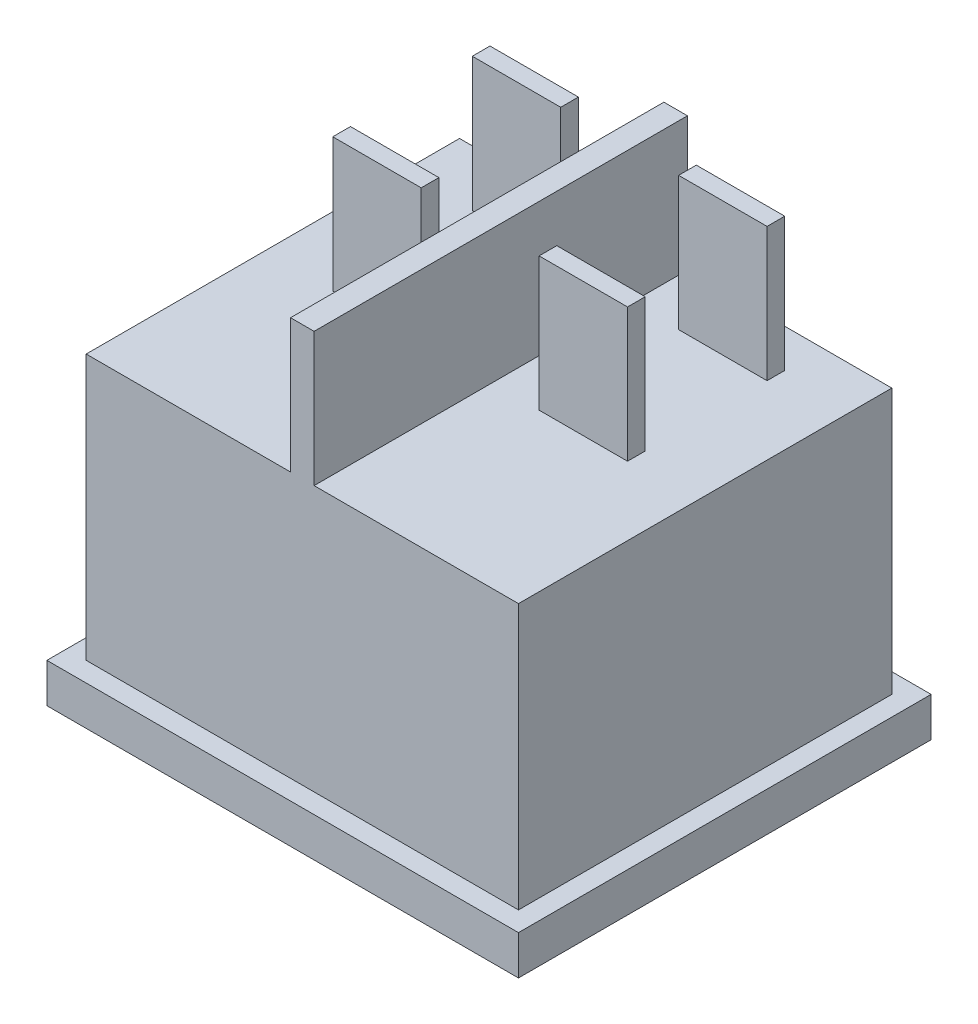
SolidWorks part; units mm, degrees
ref_plane "Front Plane" through (0, 0, 0) normal (0, 0, 1) x (1, 0, 0)
ref_plane "Top Plane" through (0, 0, 0) normal (0, 1, 0) x (1, 0, 0)
ref_plane "Right Plane" through (0, 0, 0) normal (1, 0, 0) x (0, 0, -1)
sketch "Sketch1" plane through (0, 0, 0) normal (0, 1, 0) x (1, 0, 0)
  line L1 (-12, -10.5) -> (12, -10.5)
  line L2 (-12, -10.5) -> (-12, 10.5)
  line L3 (-12, 10.5) -> (12, 10.5)
  line L4 (12, -10.5) -> (12, 10.5)
  line L5 (-12, -10.5) -> (12, 10.5) construction
  line L6 (-12, 10.5) -> (12, -10.5) construction
  point P0 (0, 0)
  dimension "D1" = 24
  dimension "D2" = 21
extrude "Boss-Extrude1" add sketch "Sketch1" along normal blind 2
sketch "Sketch2" plane through (0, 2, 0) normal (0, 1, 0) x (1, 0, 0)
  line L1 (-11, -9.5) -> (11, -9.5)
  line L2 (-11, -9.5) -> (-11, 9.5)
  line L3 (-11, 9.5) -> (11, 9.5)
  line L4 (11, -9.5) -> (11, 9.5)
  line L5 (-11, -9.5) -> (11, 9.5) construction
  line L6 (-11, 9.5) -> (11, -9.5) construction
  point P0 (0, 0)
  dimension "D1" = 22
  dimension "D2" = 19
extrude "Boss-Extrude2" add sketch "Sketch2" along normal blind 13.5
sketch "Sketch3" plane through (0, 15.5, 0) normal (0, 1, 0) x (1, 0, 0)
  line L0 (11, 9.5) -> (-11, 9.5) construction
  line L1 (-0.6, -9.5) -> (0.6, -9.5)
  line L2 (-0.6, -9.5) -> (-0.6, 9.5)
  line L3 (-0.6, 9.5) -> (0.6, 9.5)
  line L4 (0.6, -9.5) -> (0.6, 9.5)
  line L5 (-0.6, -9.5) -> (0.6, 9.5) construction
  line L6 (-0.6, 9.5) -> (0.6, -9.5) construction
  point P0 (0, 0)
  dimension "D1" = 1.2
extrude "Boss-Extrude3" add sketch "Sketch3" along normal blind 6.8
sketch "Sketch4" plane through (0, 15.5, 0) normal (0, 1, 0) x (1, 0, 0)
  line L0 (-3, 7.55) -> (3, 7.55) construction
  line L1 (-7.5, 6.65) -> (-3, 6.65)
  line L2 (-7.5, 6.65) -> (-7.5, 7.55)
  line L3 (-7.5, 7.55) -> (-3, 7.55)
  line L4 (-3, 6.65) -> (-3, 7.55)
  line L5 (-7.5, 6.65) -> (-3, 7.55) construction
  line L6 (-7.5, 7.55) -> (-3, 6.65) construction
  line L7 (-7.5, -0.45) -> (-3, -0.45)
  line L8 (-7.5, -0.45) -> (-7.5, 0.45)
  line L9 (-7.5, 0.45) -> (-3, 0.45)
  line L10 (-3, -0.45) -> (-3, 0.45)
  line L11 (-7.5, -0.45) -> (-3, 0.45) construction
  line L12 (-7.5, 0.45) -> (-3, -0.45) construction
  line L13 (3, 6.65) -> (7.5, 6.65)
  line L14 (3, 6.65) -> (3, 7.55)
  line L15 (3, 7.55) -> (7.5, 7.55)
  line L16 (7.5, 6.65) -> (7.5, 7.55)
  line L17 (3, 6.65) -> (7.5, 7.55) construction
  line L18 (3, 7.55) -> (7.5, 6.65) construction
  line L19 (3, -0.45) -> (7.5, -0.45)
  line L20 (3, -0.45) -> (3, 0.45)
  line L21 (3, 0.45) -> (7.5, 0.45)
  line L22 (7.5, -0.45) -> (7.5, 0.45)
  line L23 (3, -0.45) -> (7.5, 0.45) construction
  line L24 (3, 0.45) -> (7.5, -0.45) construction
  point P0 (-5.25, 7.1)
  point P5 (-5.25, 0)
  point P10 (5.25, 7.1)
  point P15 (5.25, 0)
  point P20 (0, 7.55)
  point P21 (0, 0)
  dimension "D1" = 15
  dimension "D2" = 8
  dimension "D3" = 0.9
  dimension "D4" = 4.5
extrude "Boss-Extrude4" add sketch "Sketch4" along normal up to surface (6.8 mm away) up to face at (0, 22.3, 0)
